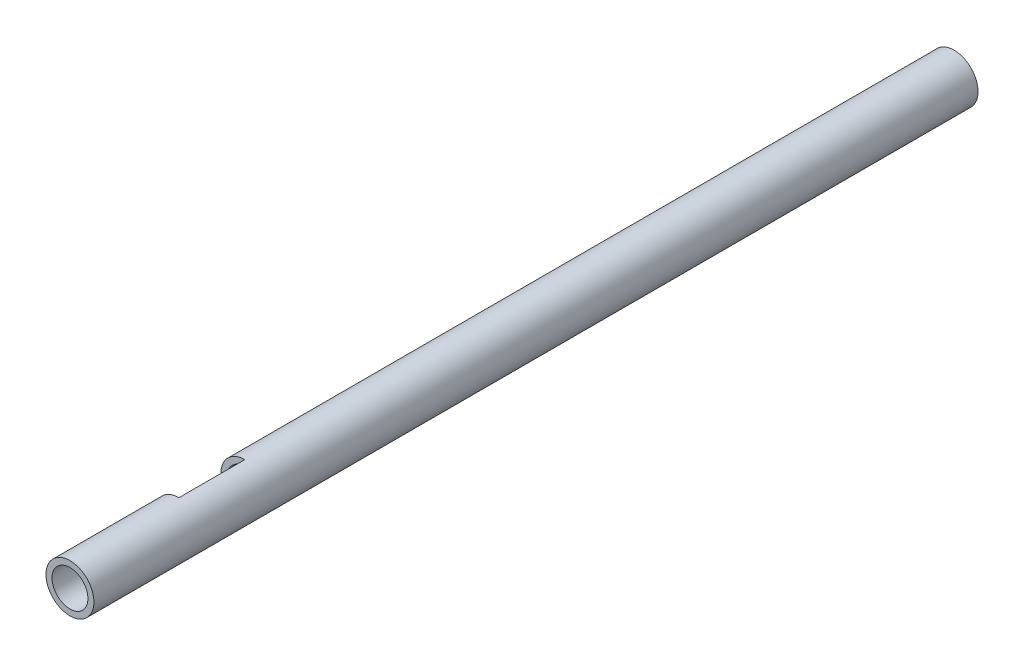
SolidWorks part; units mm, degrees
ref_plane "Front Plane" through (0, 0, 0) normal (0, 0, 1) x (1, 0, 0)
ref_plane "Top Plane" through (0, 0, 0) normal (0, 1, 0) x (1, 0, 0)
ref_plane "Right Plane" through (0, 0, 0) normal (1, 0, 0) x (0, 0, -1)
sketch "Sketch1" plane through (0, 0, 0) normal (1, 0, 0) x (0, 0, -1)
  line L0 (0, 0) -> (-101.6858, 0) construction
  line L2 (0, 20) -> (-738, 20)
  line L3 (0, 20) -> (0, 15)
  line L4 (0, 15) -> (-738, 15)
  line L5 (-738, 20) -> (-738, 15)
  dimension "D1" = 738
  dimension "D2" = 30
  dimension "D3" = 40
revolve "Revolve1" add sketch "Sketch1" angle 360 about L0
sketch "Sketch2" plane through (0, 0, 0) normal (0, 1, 0) x (1, 0, 0)
  line L0 (-37.7148, -619.5) -> (-87.2485, -619.5) construction
  line L1 (-37.7148, -677) -> (0, -677) construction
  line L2 (-37.7148, -677) -> (-37.7148, -562) construction
  line L3 (-37.7148, -562) -> (0, -562) construction
  line L4 (0, -677) -> (0, -562) construction
  line L5 (68, -562) -> (20, -562) construction
  line L6 (68, -677) -> (20, -677) construction
  line L7 (-37.7148, -592) -> (0, -592)
  line L8 (-37.7148, -592) -> (-37.7148, -647)
  line L9 (-37.7148, -647) -> (0, -647)
  line L10 (0, -592) -> (0, -647)
  point P13 (-37.7148, -619.5)
  dimension "D1" = 55
extrude "Cut-Extrude1" cut sketch "Sketch2" against normal through all and the other way through all
